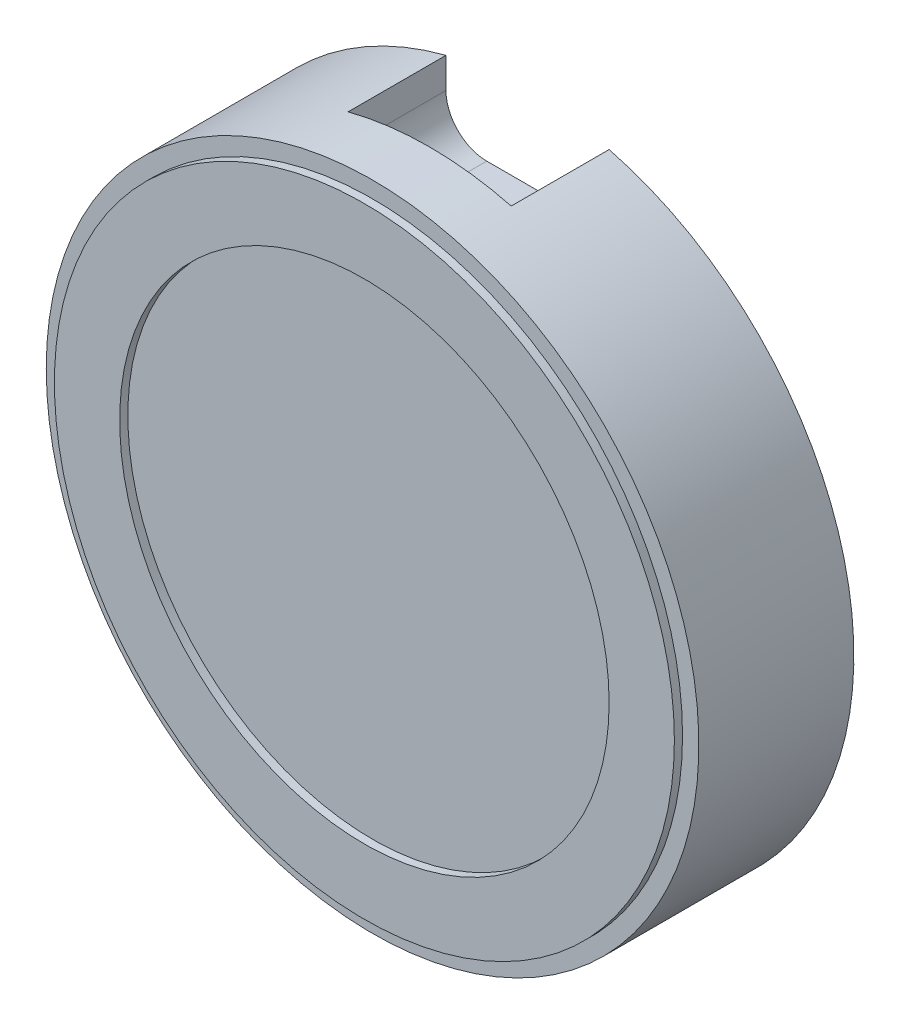
SolidWorks part; units mm, degrees
ref_plane "Front Plane" through (0, 0, 0) normal (1, 0, 0) x (0, 1, 0)
ref_plane "Top Plane" through (0, 0, 0) normal (0, 0, 1) x (0, 1, 0)
ref_plane "Right Plane" through (0, 0, 0) normal (0, 1, 0) x (-1, 0, 0)
sketch "Sketch2" plane through (0, 0, 0) normal (0, 0, 1) x (0, 1, 0)
  circle A0 centre (0, 0) radius 19
  circle A1 centre (0, 0) radius 15
  dimension "D1" = 38
  dimension "D2" = 30
extrude "Boss-Extrude1" add sketch "Sketch2" against normal blind 0.5
sketch "Sketch3" plane through (0, 0, -0.5) normal (0, 0, -1) x (1, 0, 0)
  circle A0 centre (0, 0) radius 20
  dimension "D1" = 40
extrude "Boss-Extrude2" add sketch "Sketch3" along normal blind 9.5
sketch "Sketch4" plane through (0, 0, -10) normal (0, 0, -1) x (1, 0, 0)
  line L0 (0, -20) -> (0, -15) construction
  line L5 (-5, -17.5) -> (-5, -19.3649)
  line L6 (-2.5, -15) -> (2.5, -15)
  line L8 (5, -17.5) -> (5, -19.3649)
  circle A2 centre (0, 0) radius 20 construction
  arc A3 (-5, -19.3649) -> (5, -19.3649) centre (0, 0) ccw
  arc A4 (2.5, -15) -> (5, -17.5) centre (2.5, -17.5) cw
  arc A5 (-2.5, -15) -> (-5, -17.5) centre (-2.5, -17.5) ccw
  point P7 (0, -17.5)
  point P14 (5, -15)
  point P17 (-5, -15)
  dimension "D1" = 10
  dimension "D2" = 5
  dimension "D3" = 2.5
extrude "Cut-Extrude2" cut sketch "Sketch4" against normal blind 6
sketch "Sketch5" plane through (0, 0, -10) normal (0, 0, -1) x (1, 0, 0)
  line L1 (8.8388, -8.8388) -> (8.8388, 8.8388) construction
  line L2 (8.8388, 8.8388) -> (-8.8388, 8.8388) construction
  line L3 (-8.8388, 8.8388) -> (-8.8388, -8.8388) construction
  line L4 (-8.8388, -8.8388) -> (8.8388, -8.8388) construction
  circle A0 centre (0, 0) radius 12.5 construction
  point P2 (8.8388, -8.8388)
  point P3 (8.8388, 8.8388)
  point P4 (-8.8388, 8.8388)
  point P5 (-8.8388, -8.8388)
  dimension "D1" = 25
hole_wizard "M3 Clearance Hole1" positions "Sketch5" profile "Sketch6" hole size "M3" standard "ANSI Metric"
sketch "Sketch6" plane through (-8.8388, 8.8388, -10) normal (1, 0, 0) x (0, 1, 0)
  line L0 (0, 0) -> (0, 6.0215)
  line L1 (0, 6.0215) -> (1.7, 5)
  line L2 (1.7, 5) -> (1.7, 0)
  line L5 (1.7, 0) -> (0, 0)
  line L10 (0, 6.0215) -> (-1.7, 5) construction
  line L11 (0, -6.35) -> (0, 107.95) construction
  dimension "Hole Dia." = 3.4
  dimension "Hole Depth" = 5
  dimension "Drill Angle" = 118
